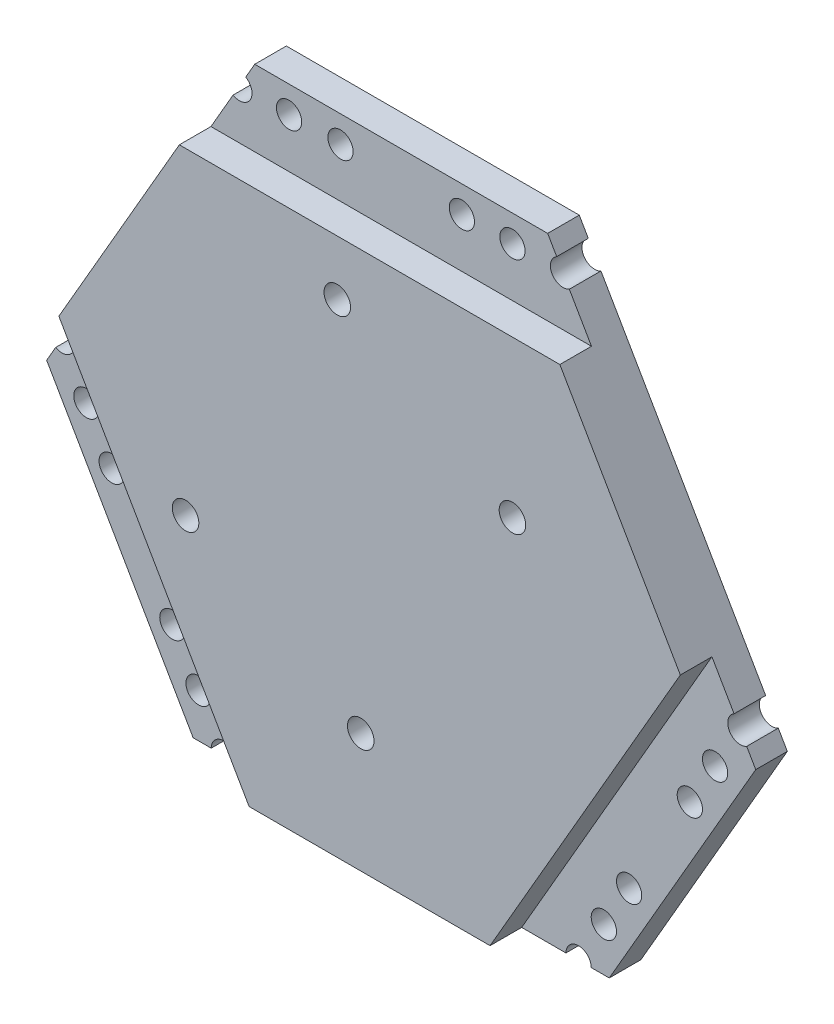
SolidWorks part; units mm, degrees
material "ABS"
ref_plane "前基準面" through (0, 0, 0) normal (0, 0, 1) x (1, 0, 0)
ref_plane "上基準面" through (0, 0, 0) normal (0, 1, 0) x (1, 0, 0)
ref_plane "右基準面" through (0, 0, 0) normal (1, 0, 0) x (0, 0, -1)
sketch "草圖1" plane through (0, 0, 0) normal (0, 0, 1) x (1, 0, 0)
  line L0 (29.3027, 33.7186) -> (37.3027, 33.7186) construction
  line L1 (45.3027, 33.7186) -> (-5.8973, 33.7186)
  line L2 (-5.8973, 33.7186) -> (-33.9573, -14.8827)
  line L3 (-33.9573, -14.8827) -> (-5.8973, 33.7186)
  line L7 (-33.9573, -14.8827) -> (-8.3573, -59.2232)
  line L8 (-8.3573, -59.2232) -> (-33.9573, -14.8827)
  line L9 (-8.3573, -59.2232) -> (47.7627, -59.2232)
  line L10 (47.7627, -59.2232) -> (73.3627, -14.8827)
  line L11 (73.3627, -14.8827) -> (45.3027, 33.7186)
  line L12 (73.3627, -14.8827) -> (69.3627, -21.8109) construction
  line L13 (-10.3973, 37.9244) -> (49.8027, 37.9244)
  line L14 (-10.3973, 37.9244) -> (-10.3973, 25.9244)
  line L15 (-10.3973, 25.9244) -> (49.8027, 25.9244)
  line L16 (49.8027, 37.9244) -> (49.8027, 25.9244)
  line L17 (-29.4573, -7.0885) -> (0.6427, -59.2232)
  line L18 (0.6427, -59.2232) -> (-9.7496, -65.2232)
  line L19 (-9.7496, -65.2232) -> (-39.8496, -13.0885)
  line L20 (-39.8496, -13.0885) -> (-29.4573, -7.0885)
  line L21 (55.7627, -45.3668) -> (51.7627, -52.295) construction
  line L22 (68.8627, -7.0885) -> (38.7627, -59.2232)
  line L23 (38.7627, -59.2232) -> (49.155, -65.2232)
  line L24 (49.155, -65.2232) -> (79.255, -13.0885)
  line L25 (79.255, -13.0885) -> (68.8627, -7.0885)
  circle A0 centre (-5.8973, 33.7186) radius 2
  circle A1 centre (1.9623, 33.7186) radius 2
  circle A2 centre (10.1027, 33.7186) radius 2
  circle A4 centre (29.3027, 33.7186) radius 2
  circle A8 centre (-33.9573, -14.8827) radius 2
  circle A9 centre (-30.0977, -21.8109) radius 2
  circle A10 centre (-26.0977, -28.7391) radius 2
  circle A12 centre (-16.4977, -45.3668) radius 2
  circle A13 centre (-12.3573, -52.295) radius 2
  circle A14 centre (-8.3573, -59.2232) radius 2
  circle A15 centre (47.7627, -59.2232) radius 2
  circle A18 centre (55.7627, -45.3668) radius 2
  circle A22 centre (37.3027, 33.7186) radius 2
  circle A23 centre (45.3027, 33.7186) radius 2
  circle A24 centre (73.3627, -14.8827) radius 2
  circle A25 centre (69.3627, -21.8109) radius 2
  circle A26 centre (65.3627, -28.7391) radius 2
  circle A27 centre (51.7627, -52.295) radius 2
  dimension "D1" = 4
  dimension "D6" = 4
  dimension "D10" = 4
  dimension "D13" = 19.2
  dimension "D11" = 4
  dimension "D15" = 19.2
  dimension "D7" = 19.2
  dimension "D17" = 8
  dimension "D2" = 8
  dimension "D3" = 120
  dimension "D4" = 120
  dimension "D5" = 56.12
  dimension "D8" = 120
  dimension "D9" = 56.12
  dimension "D12" = 8
  dimension "D16" = 56.12
  dimension "D18" = 4.5
  dimension "D19" = 4.5
  dimension "D20" = 60.2
  dimension "D21" = 12
  dimension "D22" = 90
  dimension "D23" = 180
  dimension "D24" = 12
  dimension "D25" = 4.5
  dimension "D26" = 4.5
  dimension "D27" = 8
  dimension "D28" = 12
  dimension "D29" = 60.2
  dimension "D30" = 90
  dimension "D31" = 4.5
  dimension "D14" = 3
extrude "填料-伸長4" add sketch "草圖1" along normal blind 10 contours L22 L11 L15 L3 L17 L9 | A23 L1 A22 A4 A2 A1 A0 L3 L15 L11 | A23 L11 L16 L13 L14 L3 A0 L1 A1 A2 A4 A22 | A14 L8 A13 A12 A10 A9 A8 L2 L20 L19 L18 L9 | A14 L9 L17 L2 A8 L8 A9 A10 A12 A13 | A27 L10 A15 L9 L23 L24 L25 L11 A24 A25 A26 A18 | A27 L10 A18 A26 A25 A24 L11 L22 L9 A15
sketch "草圖2" plane through (0, 0, 0) normal (0, 0, -1) x (-1, 0, 0)
  line L0 (10.3973, 25.9244) -> (29.4573, -7.0885) construction
  circle A0 centre (9.4107, -24.3667) radius 2.1
  circle A1 centre (-14.5893, 17.2026) radius 2.1
  circle A2 centre (-42.3021, 1.2026) radius 2.1
  circle A3 centre (-18.3021, -40.3667) radius 2.1
  point P4 (19.9273, 9.4179)
  dimension "D1" = 26
  dimension "D2" = 26
  dimension "D3" = 48
  dimension "D4" = 35.3836
  dimension "D6" = 4.2
  dimension "D7" = 4.2
  dimension "D5" = 2
extrude "除料-伸長1" cut sketch "草圖2" against normal through all
sketch "草圖4" plane through (0, 0, 10) normal (0, 0, 1) x (1, 0, 0)
  line L0 (38.7627, -59.2232) -> (49.155, -65.2232)
  line L1 (-10.3973, 37.9244) -> (49.8027, 37.9244)
  line L2 (-10.3973, 37.9244) -> (-10.3973, 25.9244)
  line L3 (-10.3973, 25.9244) -> (49.8027, 25.9244)
  line L4 (49.8027, 37.9244) -> (49.8027, 25.9244)
  line L5 (38.7627, -59.2232) -> (68.8722, -7.072)
  line L6 (49.155, -65.2232) -> (79.2645, -13.072)
  line L7 (68.8722, -7.072) -> (79.2645, -13.072)
  line L8 (-29.4573, -7.0885) -> (-39.8496, -13.0885)
  line L9 (-29.4573, -7.0885) -> (0.9201, -59.7038)
  line L10 (-39.8496, -13.0885) -> (-9.4722, -65.7038)
  line L11 (0.9201, -59.7038) -> (-9.4722, -65.7038)
extrude "除料-伸長2" cut sketch "草圖4" against normal blind 5
sketch "草圖7" plane through (-19.0236, 10.9833, 0) normal (-0.866, 0.5, 0) x (0, 0, 1)
  line L0 (0, -5.7866) -> (10, -5.7866)
  line L1 (0, -5.7866) -> (0, 46.268)
  line L2 (10, -5.7866) -> (10, 46.268)
  line L3 (0, 46.268) -> (10, 46.268)
  line L4 (0, 17.2525) -> (0, -20.8675) construction
  line L5 (10, 17.2525) -> (10, -20.8675) construction
  line L6 (0, -5.7866) -> (10, -5.7866)
  line L7 (0, -5.7866) -> (0, -53.8162)
  line L8 (10, -5.7866) -> (10, -53.8162)
  line L9 (0, -53.8162) -> (10, -53.8162)
  line M2 (0, -20.8675) -> (5, -20.8675)
  line M3 (5, -20.8675) -> (10, -20.8675)
  line M5 (10, 17.2525) -> (5, 17.2525)
  line M6 (5, 17.2525) -> (0, 17.2525)
extrude "除料-伸長9" cut sketch "草圖7" along direction (-0.866, 0.5, 0) on the side of the normal through all contours L7 L9 L8 M3 M2 | L3 L1 L2 M6 M5
sketch "草圖8" plane through (0, 0, 0) normal (0, 0, -1) x (-1, 0, 0)
  line L0 (-20.7041, -30.2064) -> (1.8126, -17.2064)
  line L1 (-20.7041, -30.2064) -> (-36.7041, -2.4936)
  line L2 (1.8126, -17.2064) -> (-14.1874, 10.5064)
  line L3 (-36.7041, -2.4936) -> (-14.1874, 10.5064)
  circle A0 centre (-18.3021, -40.3667) radius 2.1 construction
  circle A1 centre (9.4107, -24.3667) radius 2.1 construction
  circle A4 centre (9.4107, -24.3667) radius 2.1 construction
  dimension "D3" = 10
  dimension "D4" = 10
  dimension "D5" = 3
  dimension "D1" = 32
  dimension "D2" = 26
extrude "填料-伸長5" add sketch "草圖8" along normal blind 3
sketch "草圖9" plane through (0, 0, -3) normal (0, 0, -1) x (-1, 0, 0)
  line L0 (-20.338, -28.8404) -> (0.4466, -16.8404)
  line L1 (-20.338, -28.8404) -> (-35.338, -2.8596)
  line L2 (0.4466, -16.8404) -> (-14.5534, 9.1404)
  line L3 (-35.338, -2.8596) -> (-14.5534, 9.1404)
  line L4 (-14.1874, 10.5064) -> (-36.7041, -2.4936) construction
  line L6 (-36.7041, -2.4936) -> (-20.7041, -30.2064) construction
  dimension "D1" = 30
  dimension "D2" = 24
  dimension "D3" = 1
  dimension "D4" = 1
  dimension "D5" = 1
extrude "除料-伸長10" cut sketch "草圖9" against normal blind 6
fillet "圓角1" radius 2 4 edges at (14.5534, 9.1404, 0) (-0.4466, -16.8404, 0) (35.338, -2.8596, 0) (20.338, -28.8404, 0)
fillet "圓角2" radius 2 4 edges at (-1.8126, -17.2064, -1.5) (14.1874, 10.5064, -1.5) (36.7041, -2.4936, -1.5) (20.7041, -30.2064, -1.5)
sketch "草圖10" plane through (0, 0, 3) normal (0, 0, -1) x (-1, 0, 0)
  line L0 (-3.3034, -10.3452) -> (-10.8034, 2.6452)
  line L1 (-3.3034, -10.3452) -> (-24.0879, -22.3451)
  line L2 (-16.2855, 8.1404) -> (-33.606, -1.8596) construction
  line L3 (-34.338, -4.5917) -> (-21.338, -27.1083) construction
  line L4 (-10.8034, 2.6452) -> (-31.5879, -9.3547)
  line L5 (-24.0879, -22.3451) -> (-31.5879, -9.3547)
  line L6 (-0.5534, -15.1083) -> (-13.5534, 7.4083) construction
  circle A0 centre (-29.1909, -4.5067) radius 0.65
  circle A1 centre (-16.2005, 2.9933) radius 0.65
  circle A2 centre (-5.7005, -15.1933) radius 0.65
  circle A3 centre (-18.6909, -22.6933) radius 0.65
  dimension "D1" = 1.3
  dimension "D4" = 4.5
  dimension "D6" = 3
  dimension "D7" = 3
  dimension "D5" = 4.5
  dimension "D2" = 2
  dimension "D3" = 2
extrude "除料-伸長11" cut sketch "草圖10" against normal blind 6
sketch "草圖12" plane through (48.5776, 28.0463, 0) normal (0.866, 0.5, 0) x (0, 0, -1)
  line L0 (0, -23.6856) -> (-10, -23.6856)
  line L1 (0, -23.6856) -> (0, -70.3801)
  line L2 (-10, -23.6856) -> (-10, -70.3801)
  line L3 (0, -70.3801) -> (-10, -70.3801)
  line L4 (0, -40.5702) -> (0, -2.4502) construction
  line L5 (-10, -40.5702) -> (-10, -2.4502) construction
  line L6 (0, -23.6856) -> (-10, -23.6856)
  line L7 (0, -23.6856) -> (0, 27.878)
  line L8 (-10, -23.6856) -> (-10, 27.878)
  line L9 (0, 27.878) -> (-10, 27.878)
  line M2 (0, -2.4502) -> (-5, -2.4502)
  line M3 (-5, -2.4502) -> (-10, -2.4502)
  line M5 (-10, -40.5702) -> (-5, -40.5702)
  line M6 (-5, -40.5702) -> (0, -40.5702)
extrude "除料-伸長12" cut sketch "草圖12" along normal through all contours L3 L1 L2 M6 M5 | L7 L9 L8 M3 M2
sketch "草圖13" plane through (0, -59.2232, 0) normal (0, -1, 0) x (1, 0, 0)
  line L0 (19.7027, 10) -> (19.7027, 0)
  line L1 (19.7027, 10) -> (-25.3386, 10)
  line L2 (19.7027, 0) -> (-25.3386, 0)
  line L3 (-25.3386, 10) -> (-25.3386, 0)
  line L4 (0.6427, 10) -> (38.7627, 10) construction
  line L5 (0.6427, 0) -> (38.7627, 0) construction
  line L6 (19.7027, 10) -> (19.7027, 0)
  line L7 (19.7027, 10) -> (66.2602, 10)
  line L8 (19.7027, 0) -> (66.2602, 0)
  line L9 (66.2602, 10) -> (66.2602, 0)
  line M2 (38.7627, 0) -> (38.7627, 5)
  line M3 (38.7627, 5) -> (38.7627, 10)
  line M5 (0.6427, 10) -> (0.6427, 5)
  line M6 (0.6427, 5) -> (0.6427, 0)
extrude "除料-伸長13" cut sketch "草圖13" along normal through all contours L9 L7 L8 M3 M2 | L1 L3 L2 M6 M5
